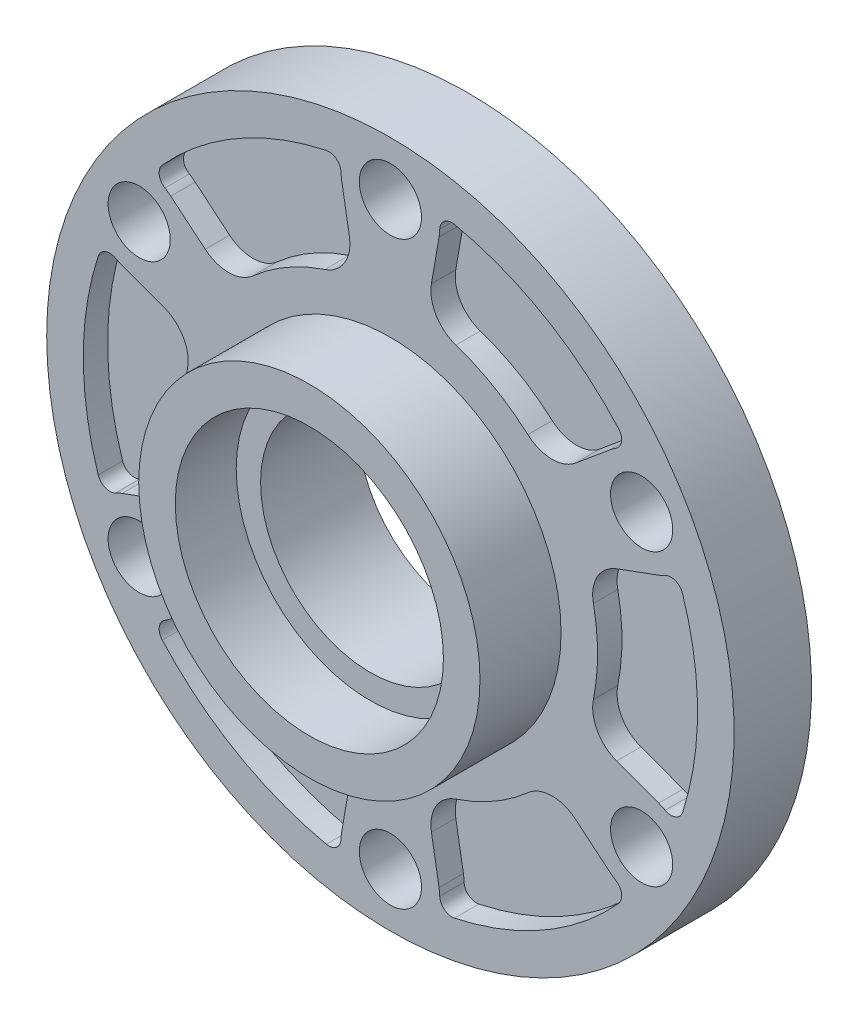
SolidWorks part; units mm, degrees
ref_plane "Plan de face" through (0, 0, 0) normal (0, 0, 1) x (1, 0, 0)
ref_plane "Plan de dessus" through (0, 0, 0) normal (0, 1, 0) x (1, 0, 0)
ref_plane "Plan de droite" through (0, 0, 0) normal (1, 0, 0) x (0, 0, -1)
sketch "Esquisse1" plane through (0, 0, 0) normal (0, 0, 1) x (1, 0, 0)
  circle A0 centre (0, 0) radius 28.2
  circle A1 centre (0, 0) radius 9
  dimension "D1" = 56.4
  dimension "D2" = 18
extrude "Boss.-Extru.1" add sketch "Esquisse1" along normal blind 13
sketch "Esquisse2" plane through (0, 0, 13) normal (0, 0, 1) x (1, 0, 0)
  circle A0 centre (0, 0) radius 14
  circle A1 centre (0, 0) radius 28.2 construction
  circle A2 centre (0, 0) radius 28.2
  dimension "D1" = 28
extrude "Enlèv. mat.-Extru.1" cut sketch "Esquisse2" against normal blind 6.65
sketch "Esquisse3" plane through (0, 0, 6.35) normal (0, 0, 1) x (1, 0, 0)
  line L0 (0, 0) -> (0, 23.8) construction
  circle A0 centre (0, 23.8) radius 2.55
  dimension "D1" = 5.1
  dimension "D2" = 23.8
extrude "Enlèv. mat.-Extru.2" cut sketch "Esquisse3" against normal through all
pattern_circular "Répétition circulaire1" count 6 over 360 about axis through (0, 0, 0) along (0, 0, 1) of "Enlèv. mat.-Extru.2"
sketch "Esquisse4" plane through (0, 0, 6.35) normal (0, 0, 1) x (1, 0, 0)
  line L0 (-18.5572, 6.8286) -> (-22.01, 8.0992)
  line L1 (-18.5572, -6.8286) -> (-22.01, -8.0992)
  circle A2 centre (0, 0) radius 25.2
  arc A3 (-23.9721, 7.7702) -> (-23.9721, -7.7702) centre (0, 0) ccw
  circle A21 centre (-20.6114, 11.9) radius 4.05
  arc A22 (-22.5437, 8.3407) -> (-22.01, 8.0992) centre (-20.6114, 11.9) ccw
  circle A24 centre (-20.6114, -11.9) radius 4.05
  arc A25 (-22.01, -8.0992) -> (-22.5437, -8.3407) centre (-20.6114, -11.9) ccw
  arc A26 (-22.5437, 8.3407) -> (-23.9721, 7.7702) centre (-23.0209, 7.4619) ccw
  circle A27 centre (0, 0) radius 17
  arc A28 (-16.6542, 3.4112) -> (-16.6542, -3.4112) centre (0, 0) ccw
  arc A29 (-23.9721, -7.7702) -> (-22.5437, -8.3407) centre (-23.0209, -7.4619) ccw
  arc A30 (-16.6542, 3.4112) -> (-18.5572, 6.8286) centre (-19.5932, 4.0132) ccw
  arc A31 (-18.5572, -6.8286) -> (-16.6542, -3.4112) centre (-19.5932, -4.0132) ccw
  dimension "D5" = 1
  dimension "D6" = 1
  dimension "D7" = 3
  dimension "D8" = 3
  dimension "D9" = 3.6792
  dimension "D10" = 3.6792
  dimension "D1" = 3
  dimension "D2" = 1.5
  dimension "D3" = 1.5
  dimension "D4" = 3
extrude "Enlèv. mat.-Extru.3" cut sketch "Esquisse4" against normal blind 2
pattern_circular "Répétition circulaire2" count 6 over 360 about axis through (0, 0, 0) along (0, 0, 1) of "Enlèv. mat.-Extru.3"
ref_plane "Plan1" through (0, 0, 3.175) normal (0, 0, 1) x (1, 0, 0)
mirror "Symétrie1" about plane through (0, 0, 3.175) normal (0, 0, 1) of "Répétition circulaire2", "Enlèv. mat.-Extru.3"
sketch "Esquisse5" plane through (0, 0, 13) normal (0, 0, 1) x (1, 0, 0)
  circle A0 centre (0, 0) radius 11
  dimension "D1" = 22
extrude "Enlèv. mat.-Extru.4" cut sketch "Esquisse5" against normal blind 5
